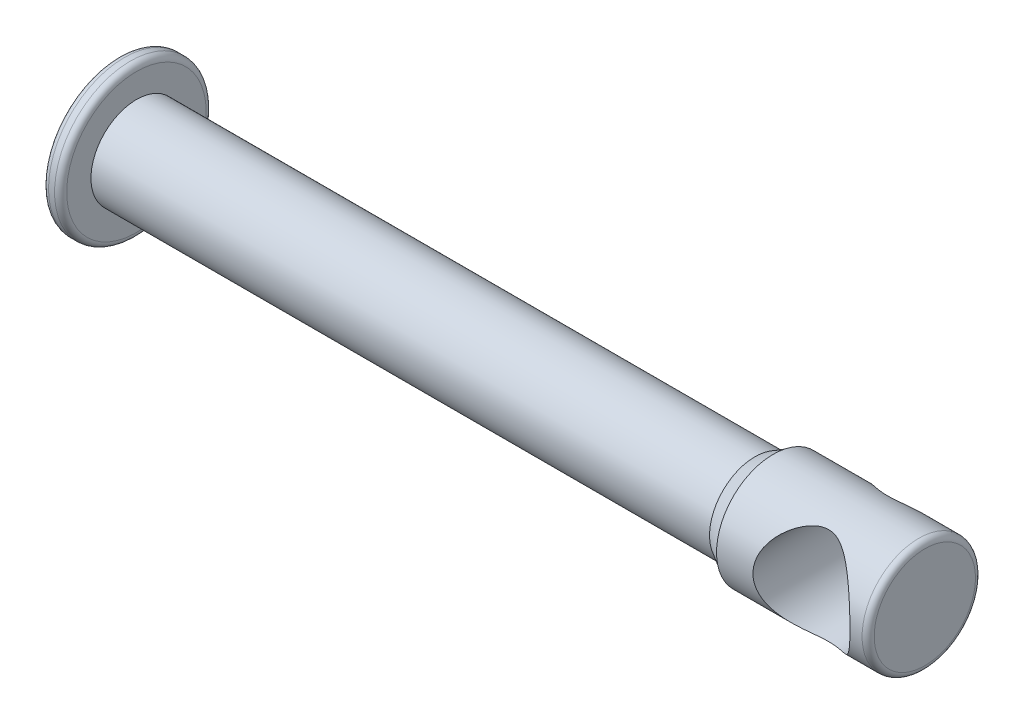
SolidWorks part; units mm, degrees
ref_plane "Front Plane" through (0, 0, 0) normal (0, 0, 1) x (1, 0, 0)
ref_plane "Top Plane" through (0, 0, 0) normal (0, 1, 0) x (1, 0, 0)
ref_plane "Right Plane" through (0, 0, 0) normal (1, 0, 0) x (0, 0, -1)
sketch "Sketch1" plane through (0, 0, 0) normal (0, 1, 0) x (1, 0, 0)
  line L0 (0, 0) -> (0, 12.5)
  line L1 (0, 12.5) -> (3, 12.5)
  line L2 (3, 12.5) -> (3, 7.5)
  line L3 (3, 7.5) -> (108, 7.5)
  line L4 (108, 7.5) -> (108, 9.35)
  line L5 (108, 9.35) -> (133, 9.35)
  line L6 (133, 9.35) -> (133, 0)
  line L7 (133, 0) -> (0, 0)
  point P6 (117.1618, 0)
  dimension "D1" = 12.5
  dimension "D2" = 9.35
  dimension "D3" = 3
  dimension "D4" = 105
  dimension "D5" = 25
  dimension "D6" = 7.5
revolve "Revolve1" add sketch "Sketch1" angle 360 about L7
chamfer "Chamfer1" distance 3 angle 30 1 edges at (108, 0, -7.5)
sketch "Sketch2" plane through (0, 0, 0) normal (0, 0, 1) x (1, 0, 0)
  line L0 (108, 0) -> (122, 0) construction
  line L1 (108, 9.2321) -> (108, -9.2321) construction
  line L2 (133, -9.35) -> (133, 9.35) construction
  circle A0 centre (122, 0) radius 8
  dimension "D2" = 16
  dimension "D1" = 11
extrude "Cut-Extrude1" cut sketch "Sketch2" against normal through all both and the other way through all
fillet "Fillet1" radius 1 3 edges at (3, 0, -12.5) (0, 0, -12.5) (133, 0, -9.35)
